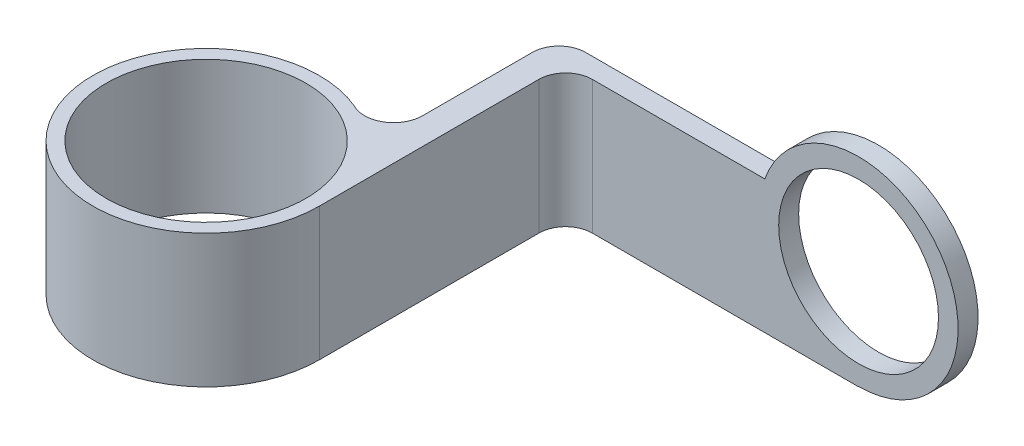
SolidWorks part; units mm, degrees
ref_plane "Front Plane" through (0, 0, 0) normal (0, 0, 1) x (1, 0, 0)
ref_plane "Top Plane" through (0, 0, 0) normal (0, 1, 0) x (1, 0, 0)
ref_plane "Right Plane" through (0, 0, 0) normal (1, 0, 0) x (0, 0, -1)
sketch "Sketch1" plane through (0, 0, 0) normal (0, 1, 0) x (1, 0, 0)
  line L0 (-40.3574, 33) -> (-40.3574, 0)
  line L1 (-44.3574, 36) -> (-44.3574, 19.5017)
  line L3 (-40.3574, 40) -> (3.6426, 40)
  line L4 (3.6426, 40) -> (3.6426, 37)
  line L5 (3.6426, 37) -> (-36.3574, 37)
  circle A0 centre (-57.3574, 0) radius 17
  circle A1 centre (-57.3574, 0) radius 15
  arc A2 (-44.3574, 36) -> (-40.3574, 40) centre (-40.3574, 36) cw
  arc A3 (-40.3574, 33) -> (-36.3574, 37) centre (-36.3574, 33) cw
  arc A4 (-50.7802, 15.6761) -> (-44.3574, 19.5017) centre (-48.7252, 19.5304) ccw
  dimension "D1" = 4
extrude "Boss-Extrude2" add sketch "Sketch1" along normal blind 20 contours A4 A0 A1 | A4 A0 L0 A3 L5 L4 L3 A2 L1
sketch "Sketch3" plane through (0, 0, -40) normal (0, 0, -1) x (-1, 0, 0)
  line L1 (40.3574, 0) -> (-3.6426, 0)
  circle A2 centre (-3.6426, 15) radius 15
  circle A3 centre (-3.6426, 15) radius 12
  line M4 (40.3574, 20) -> (-3.6426, 20)
  line M5 (-3.6426, 20) -> (-3.6426, 0)
extrude "Cut-Extrude2" cut sketch "Sketch3" against normal blind 21 contours A3 M4 M5 | A3 M5 M4
sketch "Sketch4" plane through (0, 0, -40) normal (0, 0, -1) x (-1, 0, 0)
  line L0 (-3.6426, 3) -> (-3.6426, 0)
  line L1 (7.2661, 20) -> (10.4445, 20)
  line L2 (40.3574, 20) -> (7.2661, 20) construction
  arc A0 (7.2661, 20) -> (-3.6426, 3) centre (-3.6426, 15) ccw
  arc A2 (10.4445, 20) -> (-3.6426, 0.0519) centre (-3.6426, 15) ccw
  line M4 (-3.6426, 3) -> (-3.6426, 0)
  line M7 (40.3574, 20) -> (7.2661, 20)
extrude "Boss-Extrude3" add sketch "Sketch4" against normal blind 3 contours A2 A0 M7 M4
